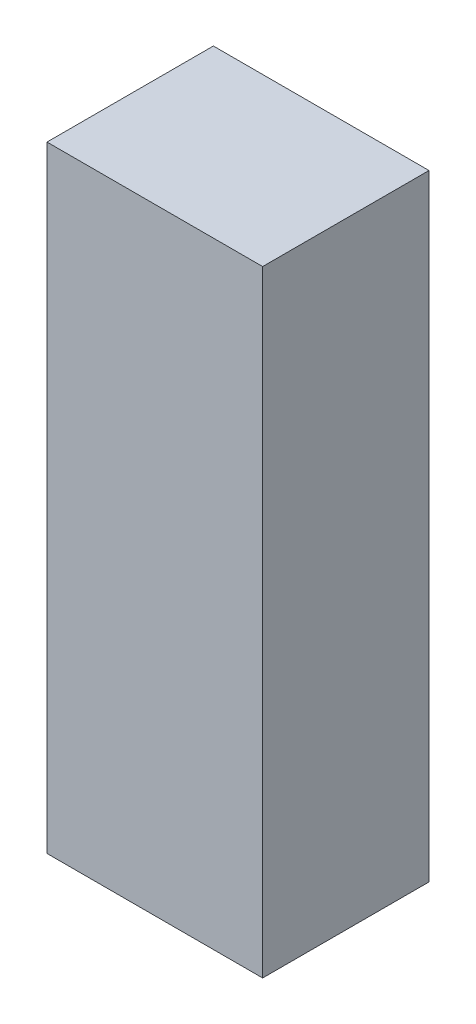
SolidWorks part; units mm, degrees
ref_plane "Front Plane" through (0, 0, 0) normal (0, 0, 1) x (1, 0, 0)
ref_plane "Top Plane" through (0, 0, 0) normal (0, 1, 0) x (1, 0, 0)
ref_plane "Right Plane" through (0, 0, 0) normal (1, 0, 0) x (0, 0, -1)
sketch "Pouch envelope profile" plane through (0, 0, 0) normal (0, 0, 1) x (1, 0, 0)
  line L0 (-17.5, -50) -> (17.5, -50)
  line L1 (17.5, -50) -> (17.5, 50)
  line L2 (17.5, 50) -> (-17.5, 50)
  line L3 (-17.5, 50) -> (-17.5, -50)
extrude "Pouch envelope" add sketch "Pouch envelope profile" along normal blind 27
